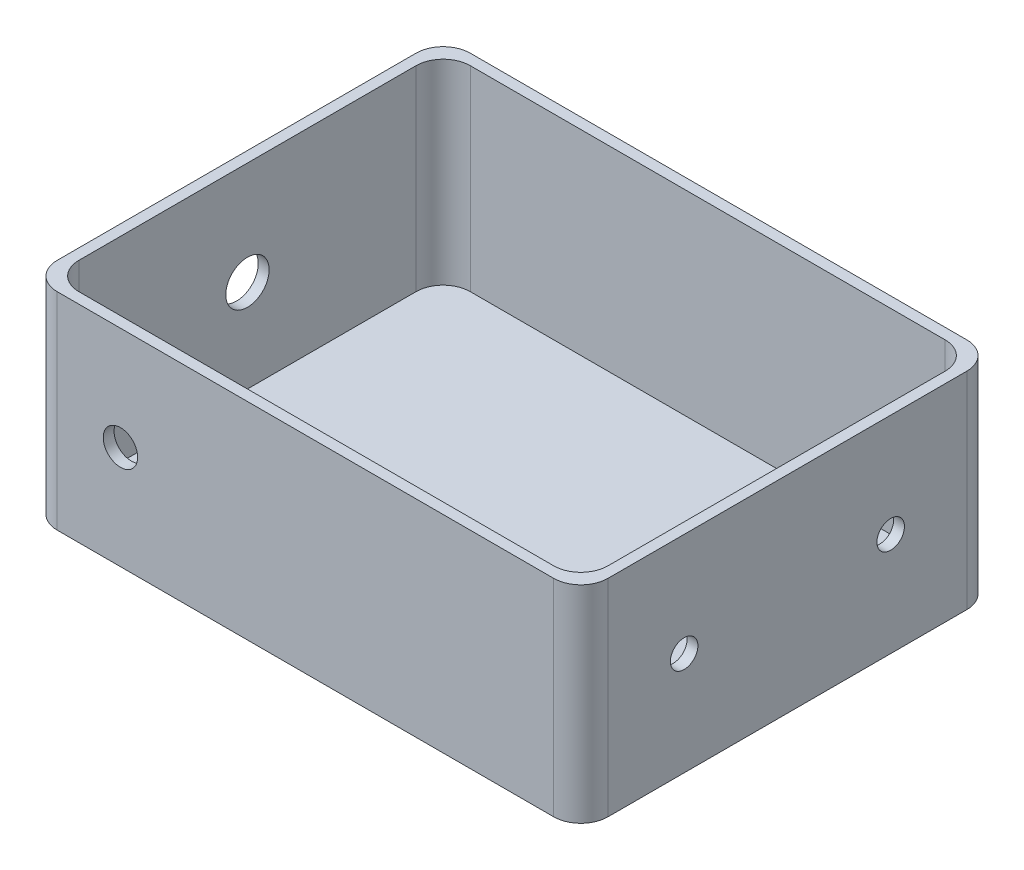
SolidWorks part; units mm, degrees
ref_plane "Front Plane" through (0, 0, 0) normal (0, 0, 1) x (1, 0, 0)
ref_plane "Top Plane" through (0, 0, 0) normal (0, 1, 0) x (1, 0, 0)
ref_plane "Right Plane" through (0, 0, 0) normal (1, 0, 0) x (0, 0, -1)
sketch "Sketch1" plane through (0, 0, 0) normal (0, 1, 0) x (1, 0, 0)
  line L1 (-50.8, 38.1) -> (50.8, 38.1)
  line L2 (-50.8, 38.1) -> (-50.8, -38.1)
  line L3 (-50.8, -38.1) -> (50.8, -38.1)
  line L4 (50.8, 38.1) -> (50.8, -38.1)
  line L5 (-50.8, 38.1) -> (50.8, -38.1) construction
  line L6 (-50.8, -38.1) -> (50.8, 38.1) construction
  point P0 (0, 0)
extrude "Boss-Extrude1" add sketch "Sketch1" along normal blind 38.1
sketch "Sketch3" plane through (0, 38.1, 0) normal (0, 1, 0) x (1, 0, 0)
  line L20 (48.8, -36.1) -> (48.8, 36.1)
  line L21 (-48.8, -36.1) -> (48.8, -36.1)
  line L22 (-48.8, 36.1) -> (-48.8, -36.1)
  line L23 (48.8, 36.1) -> (-48.8, 36.1)
  line L24 (48.8, -36.1) -> (48.8, 36.1)
  line L25 (-48.8, -36.1) -> (48.8, -36.1)
  line L26 (-48.8, 36.1) -> (-48.8, -36.1)
  line L27 (48.8, 36.1) -> (-48.8, 36.1)
  point P0 (0, 0)
  dimension "D1" = 2
extrude "Cut-Extrude1" cut sketch "Sketch3" against normal blind 36.1
sketch "Sketch5" plane through (50.8, 0, 0) normal (1, 0, 0) x (0, 0, -1)
  line L0 (0, 0) -> (0, 38.1) construction
  line L1 (-38.1, 0) -> (38.1, 0) construction
  line L2 (-38.1, 38.1) -> (38.1, 38.1) construction
  line L3 (0, 38.1) -> (-38.1, 0) construction
  line L4 (38.1, 0) -> (0, 38.1) construction
  line L5 (0, 0) -> (38.1, 38.1) construction
  line L6 (0, 0) -> (-38.1, 38.1) construction
  point P9 (-19.05, 19.05)
  point P15 (19.05, 19.05)
sketch "Sketch7" plane through (50.8, 0, 0) normal (1, 0, 0) x (0, 0, -1)
  circle A0 centre (-19.05, 19.05) radius 2.54
  circle A1 centre (19.05, 19.05) radius 2.54
extrude "Cut-Extrude2" cut sketch "Sketch7" against normal blind 2
sketch "Sketch9" plane through (-50.8, 0, 0) normal (-1, 0, 0) x (0, 0, 1)
  circle A0 centre (0, 19.05) radius 4
extrude "Cut-Extrude3" cut sketch "Sketch9" against normal blind 2
sketch "Sketch10" plane through (0, 0, 38.1) normal (0, 0, 1) x (1, 0, 0)
  line L0 (-50.8, 19.05) -> (50.8, 19.05) construction
  line L1 (-50.8, 38.1) -> (-50.8, 0) construction
  line L2 (50.8, 38.1) -> (50.8, 0) construction
sketch "Sketch11" plane through (0, 0, 38.1) normal (0, 0, 1) x (1, 0, 0)
  line L0 (-50.8, 19.05) -> (50.8, 19.05) construction
  circle A0 centre (-34.1278, 19.05) radius 3.175
extrude "Cut-Extrude4" cut sketch "Sketch11" against normal blind 2
fillet "Fillet1" radius 5 4 edges at (-50.8, 19.05, 38.1) (-50.8, 19.05, -38.1) (50.8, 19.05, -38.1) (50.8, 19.05, 38.1)
fillet "Fillet2" radius 5 4 edges at (48.8, 20.05, -36.1) (48.8, 20.05, 36.1) (-48.8, 20.05, -36.1) (-48.8, 20.05, 36.1)
sketch "Sketch12" plane through (0, 0, 0) normal (0, -1, 0) x (1, 0, 0)
  text T0 "ΔΣ" font "Century Gothic" height in points 60
extrude "Cut-Extrude5" cut sketch "Sketch12" against normal blind 1
